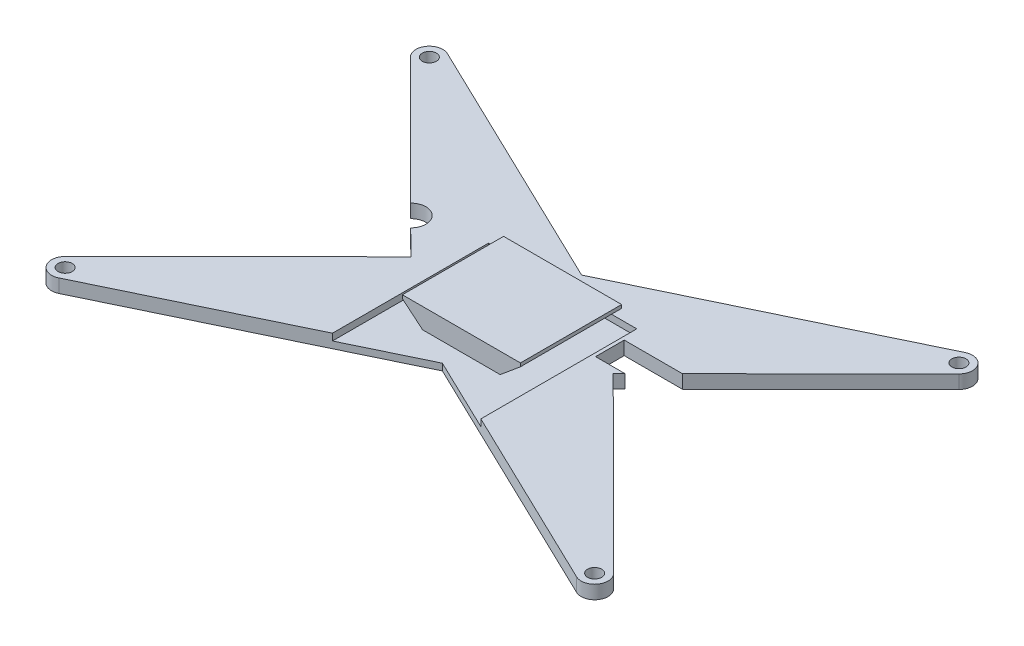
SolidWorks part; units mm, degrees
ref_plane "Front Plane" through (0, 0, 0) normal (0, 0, 1) x (1, 0, 0)
ref_plane "Top Plane" through (0, 0, 0) normal (0, 1, 0) x (1, 0, 0)
ref_plane "Right Plane" through (0, 0, 0) normal (1, 0, 0) x (0, 0, -1)
sketch "Sketch2" plane through (0, 0, 0) normal (0, 1, 0) x (1, 0, 0)
  line L0 (0, 0) -> (78.5, 0) construction
  line L1 (-78.5, 54) -> (78.5, 54)
  line L2 (-78.5, 54) -> (-78.5, -54)
  line L3 (-78.5, -54) -> (78.5, -54)
  line L4 (78.5, 54) -> (78.5, -54)
  line L5 (-78.5, 54) -> (78.5, -54) construction
  line L6 (-78.5, -54) -> (78.5, 54) construction
  line L7 (0, 20.6369) -> (76.7645, 57.6039)
  line L8 (0, 0) -> (30, 0)
  line L9 (0, -20.6369) -> (0, 20.6369)
  line L10 (0, 20.6369) -> (30, 20.6369)
  line L11 (30, -20.6369) -> (30, 20.6369)
  line L12 (30, 0) -> (81.3241, 51.1672)
  line L13 (0, -20.6369) -> (76.7645, -57.6039)
  line L14 (30, 0) -> (81.3241, -51.1672)
  line L15 (0, -20.6369) -> (30, -20.6369)
  line L16 (0, 0) -> (0, 54) construction
  line L17 (0, 20.6369) -> (-76.7645, 57.6039)
  line L18 (0, -20.6369) -> (-76.7645, -57.6039)
  line L19 (-30, 0) -> (-81.3241, -51.1672)
  line L20 (-30, 0) -> (-81.3241, 51.1672)
  circle A0 centre (78.5, 54) radius 2.1
  circle A1 centre (78.5, -54) radius 2.1
  circle A2 centre (78.5, 54) radius 4
  circle A3 centre (78.5, -54) radius 4
  circle A4 centre (78.5, -54) radius 2.1
  circle A5 centre (-78.5, -54) radius 4
  circle A6 centre (-78.5, -54) radius 2.1
  circle A7 centre (-78.5, 54) radius 2.1
  circle A8 centre (-78.5, 54) radius 4
  point P0 (0, 0)
  dimension "D3" = 4.2
  dimension "D4" = 4.2
  dimension "D5" = 8
  dimension "D1" = 157
  dimension "D2" = 108
  dimension "D6" = 30
extrude "Boss-Extrude1" add sketch "Sketch2" against normal blind 2 contours L9 L15 L11 L8 | L8 L11 L10 L9 | A2 L1 L7 L10 L11 L12 L4 | L3 A3 L4 L14 L11 L15 L13 | A2 L7 L1 | A2 L4 L12 | L4 A2 L1 A0 | L13 A3 L3 | L4 A3 L14 | A3 L4 A1 L3 | A3 L3 A1 L4 | L1 A2 L4 A0 | L1 A8 L2 L20 L19 A5 L3 L18 L9 L17 | L2 A6 L3 A5 | L3 A6 L2 A5 | A5 L18 L3 | A5 L2 L19 | A8 L2 A7 L1 | A8 L1 A7 L2 | L17 A8 L1 | L2 A8 L20
sketch "Sketch4" plane through (0, 0, 0) normal (0, 1, 0) x (1, 0, 0)
  line L1 (-11.5, 15) -> (11.5, 15)
  line L2 (-11.5, 15) -> (-11.5, -15)
  line L3 (-11.5, -15) -> (11.5, -15)
  line L4 (11.5, 15) -> (11.5, -15)
  line L5 (-11.5, 15) -> (11.5, -15) construction
  line L6 (-11.5, -15) -> (11.5, 15) construction
  point P0 (0, 0)
  dimension "D1" = 23
  dimension "D2" = 30
extrude "Boss-Extrude2" add sketch "Sketch4" along normal blind 5
sketch "Sketch5" plane through (0, 5, 0) normal (0, 1, 0) x (1, 0, 0)
  line L0 (11.5, 15) -> (-11.5, 15) construction
  line L1 (-17.5, -15) -> (17.5, -15)
  line L2 (-17.5, -15) -> (-17.5, 15)
  line L3 (-17.5, 15) -> (17.5, 15)
  line L4 (17.5, -15) -> (17.5, 15)
  line L5 (-17.5, -15) -> (17.5, 15) construction
  line L6 (-17.5, 15) -> (17.5, -15) construction
  point P0 (0, 0)
  dimension "D1" = 35
extrude "Boss-Extrude3" add sketch "Sketch5" along normal blind 1
sketch "Sketch6" plane through (0, 0, 15) normal (0, 0, 1) x (1, 0, 0)
  line L0 (11.5, 0) -> (17.5, 5)
  line L1 (17.5, 5) -> (11.5, 5)
  line L2 (11.5, 5) -> (11.5, 0)
  line L3 (0, 0) -> (0, 12.4208) construction
  line L4 (-17.5, 5) -> (-11.5, 5)
  line L5 (-11.5, 0) -> (-17.5, 5)
  line L6 (-11.5, 5) -> (-11.5, 0)
extrude "Boss-Extrude4" add sketch "Sketch6" against normal blind 30
sketch "Sketch8" plane through (0, 0, 0) normal (0, 1, 0) x (1, 0, 0)
  line L0 (30, 0) -> (81.3241, 51.1672) construction
  line L1 (-22, 17.8877) -> (22, 17.8877)
  line L2 (-22, 17.8877) -> (-22, -17.8877)
  line L3 (-22, -17.8877) -> (22, -17.8877)
  line L4 (22, 17.8877) -> (22, -17.8877)
  line L5 (-22, 17.8877) -> (22, -17.8877) construction
  line L6 (-22, -17.8877) -> (22, 17.8877) construction
  line L7 (0, 20.6369) -> (76.7645, 57.6039) construction
  line L8 (0, 20.6369) -> (-76.7645, 57.6039) construction
  line L9 (30, 0) -> (81.3241, -51.1672) construction
  line L10 (0, -20.6369) -> (76.7645, -57.6039) construction
  line L11 (0, -20.6369) -> (-76.7645, -57.6039) construction
  line L12 (-30, 0) -> (-81.3241, -51.1672) construction
  line L13 (-30, 0) -> (-81.3241, 51.1672) construction
  line L14 (30, 0) -> (81.3241, 51.1672)
  line L15 (0, 20.6369) -> (76.7645, 57.6039)
  line L16 (0, 20.6369) -> (-76.7645, 57.6039)
  line L17 (30, 0) -> (81.3241, -51.1672)
  line L18 (0, -20.6369) -> (76.7645, -57.6039)
  line L19 (0, -20.6369) -> (-76.7645, -57.6039)
  line L20 (-30, 0) -> (-81.3241, -51.1672)
  line L21 (-30, 0) -> (-81.3241, 51.1672)
  line L22 (-22, -17.8877) -> (-22, -31.2313)
  line L23 (-22, -31.2313) -> (0, -20.6369)
  line L24 (22, -31.2313) -> (22, -17.8877)
  line L25 (11.5, 15) -> (-11.5, 15) construction
  line L26 (-22, 17.8877) -> (22, 17.8877)
  line L27 (-22, 17.8877) -> (-22, 15)
  line L28 (-22, 15) -> (22, 15)
  line L29 (22, 17.8877) -> (22, 15)
  circle A0 centre (78.5, 54) radius 2.1 construction
  arc A1 (81.3241, 51.1672) -> (76.7645, 57.6039) centre (78.5, 54) ccw construction
  arc A2 (-76.7645, 57.6039) -> (-81.3241, 51.1672) centre (-78.5, 54) ccw construction
  circle A3 centre (-78.5, 54) radius 2.1 construction
  circle A4 centre (-78.5, -54) radius 2.1 construction
  circle A5 centre (78.5, -54) radius 2.1 construction
  arc A6 (76.7645, -57.6039) -> (81.3241, -51.1672) centre (78.5, -54) ccw construction
  arc A7 (-81.3241, -51.1672) -> (-76.7645, -57.6039) centre (-78.5, -54) ccw construction
  circle A8 centre (78.5, 54) radius 2.1
  arc A9 (81.3241, 51.1672) -> (76.7645, 57.6039) centre (78.5, 54) ccw
  arc A10 (-76.7645, 57.6039) -> (-81.3241, 51.1672) centre (-78.5, 54) ccw
  circle A11 centre (-78.5, 54) radius 2.1
  circle A12 centre (-78.5, -54) radius 2.1
  circle A13 centre (78.5, -54) radius 2.1
  arc A14 (76.7645, -57.6039) -> (81.3241, -51.1672) centre (78.5, -54) ccw
  arc A15 (-81.3241, -51.1672) -> (-76.7645, -57.6039) centre (-78.5, -54) ccw
  point P0 (0, 0)
  circle M17 centre (78.5, 54) radius 2.1
  line M18 (0, 20.6369) -> (-76.7645, 57.6039)
  arc M19 (-76.7645, 57.6039) -> (-81.3241, 51.1672) centre (-78.5, 54) ccw
  line M20 (-81.3241, 51.1672) -> (-30, 0)
  line M21 (-30, 0) -> (-81.3241, -51.1672)
  arc M22 (-81.3241, -51.1672) -> (-76.7645, -57.6039) centre (-78.5, -54) ccw
  line M23 (-76.7645, -57.6039) -> (0, -20.6369)
  arc M25 (76.7645, -57.6039) -> (81.3241, -51.1672) centre (78.5, -54) ccw
  line M26 (81.3241, -51.1672) -> (30, 0)
  line M27 (30, 0) -> (81.3241, 51.1672)
  arc M28 (81.3241, 51.1672) -> (76.7645, 57.6039) centre (78.5, 54) ccw
  line M29 (76.7645, 57.6039) -> (0, 20.6369)
  circle M30 centre (-78.5, 54) radius 2.1
  circle M31 centre (-78.5, -54) radius 2.1
  circle M32 centre (78.5, -54) radius 2.1
  dimension "D1" = 44
extrude "Boss-Extrude5" add sketch "Sketch8" along normal blind 2 contours L24 L18 L22 L2 L1 L4 M25 M26 M27 M28 M29 M18 M19 M20 M21 M22 M23 M17 M30 M32 M31 | L27 L26 L29 L28
sketch "Sketch9" plane through (0, -2, 0) normal (0, -1, 0) x (1, 0, 0)
  line L0 (-30, 0) -> (-40.6228, -10.5904) construction
  line L1 (-30, 0) -> (-81.3241, -51.1672) construction
  line L2 (30, 0) -> (36.0196, -6.0012) construction
  line L3 (30, 0) -> (81.3241, -51.1672) construction
  line L5 (49.0196, -1.7512) -> (23.0196, -1.7512)
  line L6 (49.0196, -1.7512) -> (49.0196, -10.2512)
  line L7 (49.0196, -10.2512) -> (23.0196, -10.2512)
  line L8 (23.0196, -1.7512) -> (23.0196, -10.2512)
  line L9 (49.0196, -1.7512) -> (23.0196, -10.2512) construction
  line L10 (49.0196, -10.2512) -> (23.0196, -1.7512) construction
  circle A0 centre (-40.6228, -10.5904) radius 4.5
  dimension "D2" = 9
  dimension "D1" = 15
  dimension "D3" = 8.5
  dimension "D4" = 13
  dimension "D5" = 8.5
extrude "Cut-Extrude1" cut sketch "Sketch9" against normal blind 33
chamfer "Chamfer1" distance 0.5 angle 45 4 edges at (-78.5, -2, -51.9) (78.5, -2, -51.9) (78.5, -2, 56.1) (-78.5, -2, 56.1)
